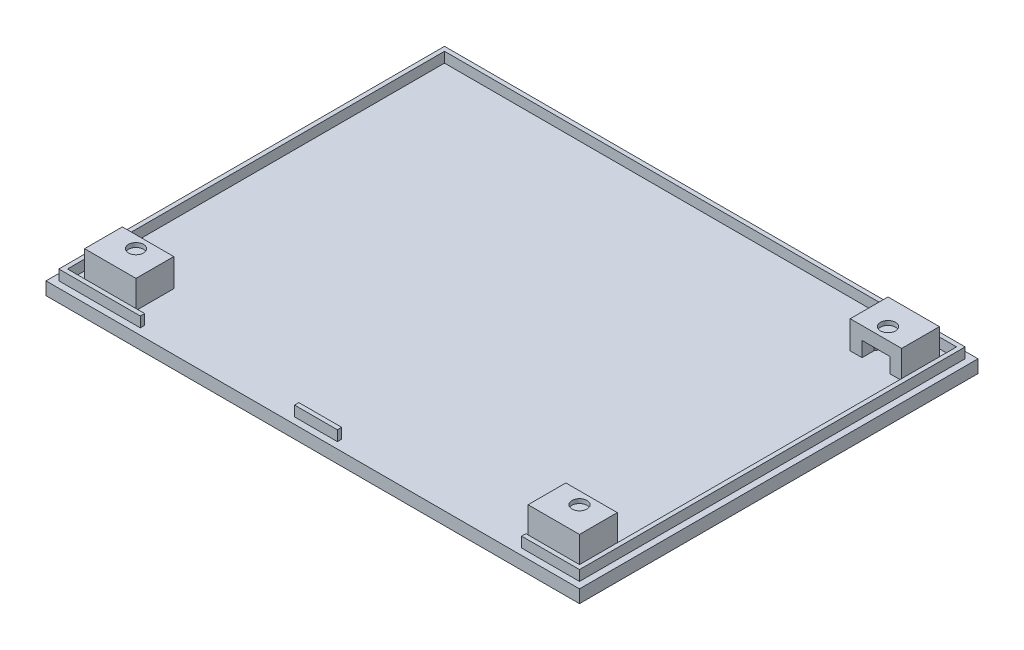
SolidWorks part; units mm, degrees
ref_plane "Спереди" through (0, 0, 0) normal (0, 0, 1) x (1, 0, 0)
ref_plane "Сверху" through (0, 0, 0) normal (0, 1, 0) x (1, 0, 0)
ref_plane "Справа" through (0, 0, 0) normal (1, 0, 0) x (0, 0, -1)
sketch "Эскиз1" plane through (0, 0, 0) normal (0, 1, 0) x (1, 0, 0)
  line L1 (-62.25, -46.5) -> (62.25, -46.5)
  line L2 (-62.25, -46.5) -> (-62.25, 46.5)
  line L3 (-62.25, 46.5) -> (62.25, 46.5)
  line L4 (62.25, -46.5) -> (62.25, 46.5)
  line L5 (-62.25, -46.5) -> (62.25, 46.5) construction
  line L6 (-62.25, 46.5) -> (62.25, -46.5) construction
  point P0 (0, 0)
  dimension "D1" = 124.5
  dimension "D2" = 93
extrude "Бобышка-Вытянуть1" add sketch "Эскиз1" along normal blind 3
sketch "Эскиз2" plane through (0, 3, 0) normal (0, 1, 0) x (1, 0, 0)
  line L2 (-60.25, -44.5) -> (-60.25, 44.5)
  line L3 (-60.25, 44.5) -> (60.25, 44.5)
  line L4 (60.25, -44.5) -> (60.25, 44.5)
  line L5 (-60.25, -44.5) -> (60.25, 44.5) construction
  line L6 (-60.25, 44.5) -> (60.25, -44.5) construction
  line L8 (-60.25, -44.5) -> (-41.75, -44.5)
  line L9 (60.25, -44.5) -> (47.25, -44.5)
  line L10 (-62.25, 46.5) -> (-62.25, -46.5) construction
  line L11 (-5.75, -44.5) -> (4.25, -44.5)
  line L12 (62.25, -46.5) -> (62.25, 46.5) construction
  point P0 (0, 0)
  point P16 (62.25, -44.9463)
  dimension "D1" = 89
  dimension "D2" = 120.5
  dimension "D3" = 20.5
  dimension "D4" = 15
  dimension "D5" = 56.5
  dimension "D6" = 58
extrude "Вытянуть-Тонкостенный1" add sketch "Эскиз2" along normal blind 2.4 thin thin type mid plane wall 1
sketch "Эскиз3" plane through (0, 3, 0) normal (0, 1, 0) x (1, 0, 0)
  line L0 (-55, -36) -> (-55, -33.1854)
  line L5 (-57.75, -42) -> (57.75, -42) construction
  line L6 (-57.75, -42) -> (-57.75, 42) construction
  line L7 (-57.75, 42) -> (57.75, 42) construction
  line L8 (57.75, -42) -> (57.75, 42) construction
  line L9 (-51.75, -36) -> (51.75, -36) construction
  line L10 (-51.75, -36) -> (-51.75, 36) construction
  line L11 (-51.75, 36) -> (51.75, 36) construction
  line L12 (51.75, -36) -> (51.75, 36) construction
  line L13 (-51.75, -36) -> (51.75, 36) construction
  line L14 (-51.75, 36) -> (51.75, -36) construction
  line L15 (-57.75, -42) -> (57.75, 42) construction
  line L16 (-57.75, 42) -> (57.75, -42) construction
  line L17 (-48.5, -36) -> (-50.125, -33.1854) construction
  line L18 (-50.125, -33.1854) -> (-53.375, -33.1854) construction
  line L19 (-53.375, -33.1854) -> (-55, -36) construction
  line L20 (-55, -36) -> (-53.375, -38.8146)
  line L21 (-53.375, -38.8146) -> (-50.125, -38.8146)
  line L22 (-50.125, -38.8146) -> (-48.5, -36)
  line L23 (-55, -33.1854) -> (-57.75, -33.1854)
  line L24 (-57.75, -33.1854) -> (-57.75, -42)
  line L25 (-57.75, -42) -> (-45.75, -42)
  line L26 (-45.75, -42) -> (-45.75, -33.1854)
  line L27 (-48.5, -36) -> (-48.5, -33.1854)
  line L28 (-48.5, -33.1854) -> (-45.75, -33.1854)
  line L29 (55, 36) -> (55, 33.1854)
  line L30 (48.5, 36) -> (50.125, 33.1854) construction
  line L31 (50.125, 33.1854) -> (53.375, 33.1854) construction
  line L32 (53.375, 33.1854) -> (55, 36) construction
  line L33 (55, 36) -> (53.375, 38.8146)
  line L34 (53.375, 38.8146) -> (50.125, 38.8146)
  line L35 (50.125, 38.8146) -> (48.5, 36)
  line L36 (55, 33.1854) -> (57.75, 33.1854)
  line L37 (57.75, 33.1854) -> (57.75, 42)
  line L38 (57.75, 42) -> (45.75, 42)
  line L39 (45.75, 42) -> (45.75, 33.1854)
  line L40 (45.75, 33.1854) -> (48.5, 33.1854)
  line L41 (48.5, 33.1854) -> (48.5, 36)
  line L42 (55, -36) -> (55, -33.1854)
  line L43 (55, -36) -> (53.375, -33.1854) construction
  line L44 (53.375, -33.1854) -> (50.125, -33.1854) construction
  line L45 (50.125, -33.1854) -> (48.5, -36) construction
  line L46 (48.5, -36) -> (50.125, -38.8146)
  line L47 (50.125, -38.8146) -> (53.375, -38.8146)
  line L48 (53.375, -38.8146) -> (55, -36)
  line L49 (55, -33.1854) -> (57.75, -33.1854)
  line L50 (57.75, -33.1854) -> (57.75, -42)
  line L55 (48.5, -36) -> (48.5, -33.1854)
  line L56 (48.5, -33.1854) -> (45.75, -33.1854)
  line L57 (45.75, -33.1854) -> (45.75, -42)
  line L58 (45.75, -42) -> (57.75, -42)
  circle A0 centre (-51.75, -36) radius 2.8146 construction
  circle A1 centre (51.75, 36) radius 2.8146 construction
  circle A2 centre (51.75, -36) radius 2.8146 construction
  point P0 (0, 0)
  point P1 (0, 0)
  point P6 (0, 0)
  dimension "D1" = 115.5
  dimension "D2" = 84
  dimension "D3" = 103.5
  dimension "D4" = 72
  dimension "D5" = 6.5
  dimension "D6" = 2.75
  dimension "D7" = 6.5
  dimension "D8" = 2.75
  dimension "D9" = 6.5
  dimension "D10" = 2.75
extrude "Бобышка-Вытянуть2" add sketch "Эскиз3" along normal blind 3.5
sketch "Эскиз4" plane through (0, 6.5, 0) normal (0, 1, 0) x (1, 0, 0)
  line L0 (-57.75, -42) -> (-57.75, -33.1854)
  line L1 (-57.75, -33.1854) -> (-45.75, -33.1854)
  line L2 (-45.75, -33.1854) -> (-45.75, -42)
  line L3 (-45.75, -42) -> (-57.75, -42)
  line L4 (-55, -36) -> (-48.5, -36) construction
  line L5 (45.75, -33.1854) -> (57.75, -33.1854)
  line L6 (45.75, -33.1854) -> (45.75, -42)
  line L7 (45.75, -42) -> (57.75, -42)
  line L8 (57.75, -33.1854) -> (57.75, -42)
  line L9 (45.75, 42) -> (57.75, 42)
  line L10 (45.75, 42) -> (45.75, 33.1854)
  line L11 (45.75, 33.1854) -> (57.75, 33.1854)
  line L12 (57.75, 42) -> (57.75, 33.1854)
  line L13 (48.5, -36) -> (55, -36) construction
extrude "Бобышка-Вытянуть3" add sketch "Эскиз4" along normal blind 3
sketch "Эскиз5" plane through (0, 9.5, 0) normal (0, 1, 0) x (1, 0, 0)
  line L0 (45.75, 42) -> (45.75, 33.1854) construction
  line L1 (57.75, 42) -> (45.75, 42) construction
  line L2 (45.75, -42) -> (57.75, -42) construction
  line L3 (45.75, -33.1854) -> (45.75, -42) construction
  line L4 (-57.75, -42) -> (-45.75, -42) construction
  line L5 (-57.75, -33.1854) -> (-57.75, -42) construction
  circle A0 centre (-51.75, -36) radius 1.75
  circle A1 centre (51.75, -36) radius 1.75
  circle A2 centre (51.75, 36) radius 1.75
  dimension "D1" = 6
  dimension "D3" = 3.5
  dimension "D4" = 6
  dimension "D5" = 6
  dimension "D6" = 3.5
  dimension "D7" = 6
  dimension "D8" = 6
  dimension "D9" = 3.5
  dimension "D2" = 6
extrude "Вырез-Вытянуть1" cut sketch "Эскиз5" against normal blind 1
